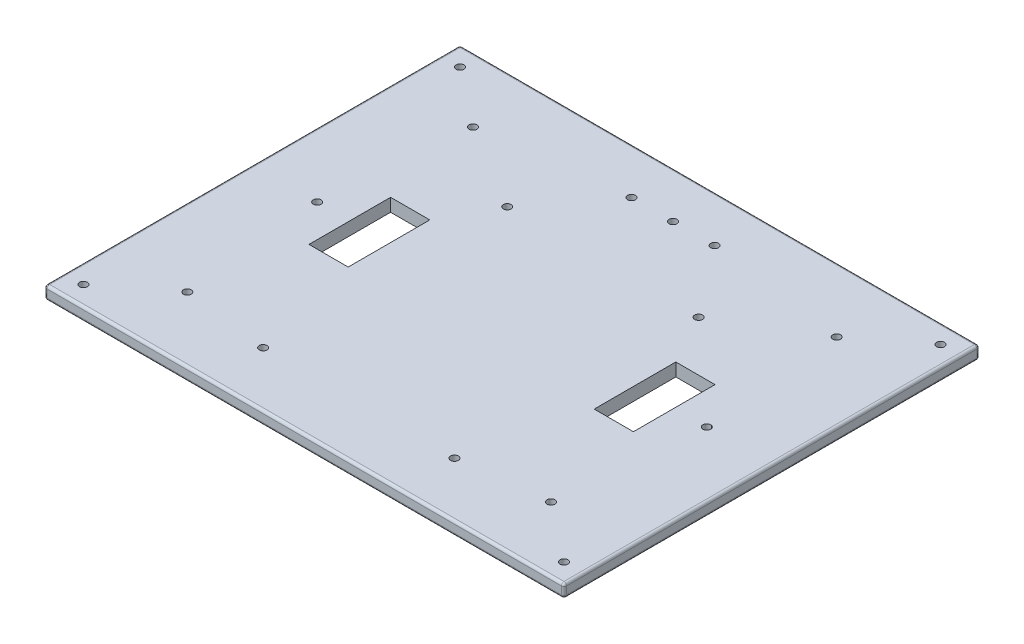
SolidWorks part; units mm, degrees
ref_plane "Front Plane" through (0, 0, 0) normal (0, 0, 1) x (1, 0, 0)
ref_plane "Top Plane" through (0, 0, 0) normal (0, 1, 0) x (1, 0, 0)
ref_plane "Right Plane" through (0, 0, 0) normal (1, 0, 0) x (0, 0, -1)
sketch "Sketch7" plane through (0, 0, 0) normal (0, 1, 0) x (1, 0, 0)
  line L1 (-100, -80) -> (100, -80)
  line L2 (-100, -80) -> (-100, 80)
  line L3 (-100, 80) -> (100, 80)
  line L4 (100, -80) -> (100, 80)
  line L5 (0, 80) -> (0, -80) construction
  line L6 (-100, 0) -> (100, 0) construction
  point P0 (0, 0)
  dimension "D1" = 160
  dimension "D2" = 200
extrude "Boss-Extrude5" add sketch "Sketch7" along normal blind 5
sketch "Sketch8" plane through (0, 0, 0) normal (0, -1, 0) x (-1, 0, 0)
  line L0 (100, -72.5) -> (70.7396, -72.5)
  line L1 (100, 80) -> (100, -80) construction
  line L3 (100, -80) -> (-100, -80) construction
  line L4 (92.5, -80) -> (92.5, -38.6452)
  circle A0 centre (92.5, -72.5) radius 1.5
  dimension "D3" = 3
  dimension "D1" = 7.5
  dimension "D2" = 7.5
extrude "Cut-Extrude2" cut sketch "Sketch8" against normal through all contours A0
mirror "Mirror4" about plane through (0, 0, 0) normal (0, 0, 1) of "Cut-Extrude2"
mirror "Mirror5" about plane through (0, 0, 0) normal (1, 0, 0) of "Mirror4", "Cut-Extrude2"
sketch "Sketch11" plane through (0, 0, 0) normal (0, -1, 0) x (-1, 0, 0)
  line L0 (0, -95.5542) -> (0, 95.5542) construction
  line L2 (-100, 80) -> (100, 80) construction
  circle A0 centre (36.83, -58.98) radius 1.5
  circle A2 centre (36.83, 35) radius 1.5
  circle A3 centre (-36.83, -58.98) radius 1.5
  circle A4 centre (-36.83, 35) radius 1.5
  point P10 (0, 0)
  dimension "D3" = 45
  dimension "D4" = 3
  dimension "D5" = 3
  dimension "D2" = 36.83
  dimension "D1" = 93.98
extrude "Cut-Extrude8" cut sketch "Sketch11" against normal through all
sketch "Sketch15" plane through (0, 0, 0) normal (0, -1, 0) x (-1, 0, 0)
  line L0 (100, -80) -> (-100, -80) construction
  line L1 (100, 80) -> (100, -80) construction
  line L2 (-2.75, 0) -> (2.75, 0) construction
  line L3 (0, 2.75) -> (0, -2.75) construction
  circle A2 centre (70, -55) radius 1.5
  circle A3 centre (70, 55) radius 1.5
  circle A4 centre (-70, 55) radius 1.5
  circle A5 centre (-70, -55) radius 1.5
  dimension "D1" = 3
  dimension "D2" = 25
  dimension "D3" = 30
extrude "Cut-Extrude13" cut sketch "Sketch15" against normal through all
sketch "Sketch17" plane through (0, 0, 0) normal (0, -1, 0) x (-1, 0, 0)
  line L0 (100, 80) -> (100, -80) construction
  line L1 (0, 2.75) -> (0, -2.75) construction
  circle A0 centre (75, 0) radius 1.5
  circle A1 centre (-75, 0) radius 1.5
  dimension "D1" = 3
  dimension "D2" = 25
extrude "Cut-Extrude16" cut sketch "Sketch17" against normal through all
sketch "Sketch18" plane through (0, 0, 0) normal (0, -1, 0) x (-1, 0, 0)
  line L0 (-100, 80) -> (100, 80) construction
  circle A0 centre (0, 62) radius 1.5
  circle A1 centre (-16, 62) radius 1.5
  dimension "D1" = 3
  dimension "D3" = 3
  dimension "D2" = 18
  dimension "D4" = 16
extrude "Cut-Extrude20" cut sketch "Sketch18" against normal through all
mirror "Mirror12" about plane through (0, 0, 0) normal (1, 0, 0) of "Cut-Extrude20"
fillet "Fillet1" radius 1 12 edges at (-100, 5, 0) (-100, 0, 0) (0, 5, -80) (-100, 2.5, -80) (0, 0, -80) (100, 5, 0) (100, 2.5, -80) (100, 0, 0) (-100, 2.5, 80) (0, 5, 80) (100, 2.5, 80) (0, 0, 80)
sketch "Sketch19" plane through (0, 5, 0) normal (0, 1, 0) x (1, 0, 0)
  line L0 (0, -2.75) -> (0, 2.75) construction
  line L1 (-62.4555, -15.7071) -> (-47.3616, -15.7071)
  line L2 (-62.4555, -15.7071) -> (-62.4555, 15.7071)
  line L3 (-62.4555, 15.7071) -> (-47.3616, 15.7071)
  line L4 (-47.3616, -15.7071) -> (-47.3616, 15.7071)
  line L5 (-62.4555, -15.7071) -> (-47.3616, 15.7071) construction
  line L6 (-62.4555, 15.7071) -> (-47.3616, -15.7071) construction
  line L7 (62.4555, 15.7071) -> (47.3616, 15.7071)
  line L8 (47.3616, -15.7071) -> (47.3616, 15.7071)
  line L9 (62.4555, -15.7071) -> (47.3616, -15.7071)
  line L10 (62.4555, -15.7071) -> (62.4555, 15.7071)
  line L11 (62.4555, 15.7071) -> (47.3616, -15.7071) construction
  line L12 (62.4555, -15.7071) -> (47.3616, 15.7071) construction
  point P0 (-54.9085, 0)
  point P11 (54.9085, 0)
extrude "Cut-Extrude21" cut sketch "Sketch19" against normal through all
